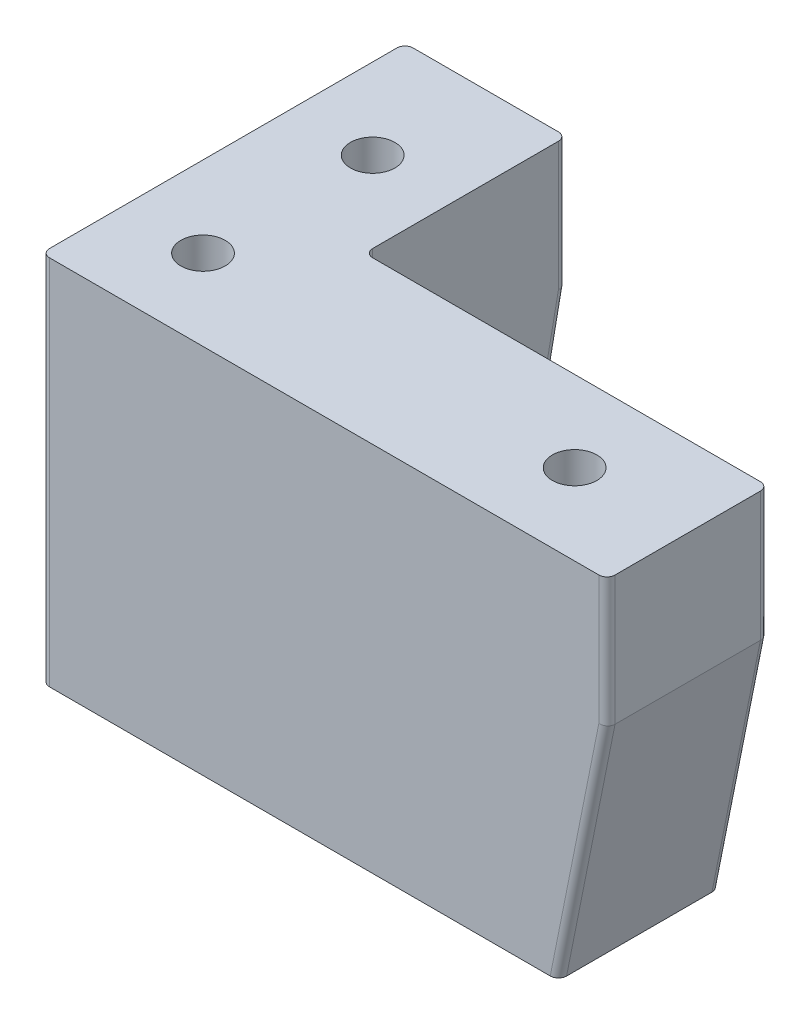
SolidWorks part; units mm, degrees
ref_plane "Front" through (0, 0, 0) normal (0, 0, 1) x (1, 0, 0)
ref_plane "Top" through (0, 0, 0) normal (0, 1, 0) x (1, 0, 0)
ref_plane "Right" through (0, 0, 0) normal (1, 0, 0) x (0, 0, -1)
sketch "Sketch1" plane through (0, 0, 0) normal (0, 1, 0) x (1, 0, 0)
  line L0 (0, 0) -> (70, 0)
  line L1 (70, 0) -> (70, 20)
  line L2 (70, 20) -> (20, 20)
  line L3 (20, 20) -> (20, 45)
  line L4 (20, 45) -> (0, 45)
  line L5 (0, 45) -> (0, 0)
  dimension "D1" = 70
  dimension "D2" = 45
  dimension "D3" = 20
extrude "Boss-Extrude1" add sketch "Sketch1" against normal blind 16
ref_plane "Plane1" through (0, -46, 0) normal (0, 1, 0) x (1, 0, 0)
sketch "Sketch5" plane through (0, -46, 0) normal (0, 1, 0) x (1, 0, 0)
  line L2 (0, 0) -> (64, 0)
  line L3 (0, 0) -> (70, 0) construction
  line L4 (0, 0) -> (0, 39)
  line L5 (0, 45) -> (0, 0) construction
  line L6 (0, 39) -> (20, 39)
  line L7 (20, 20) -> (20, 45) construction
  line L8 (20, 39) -> (20, 20)
  line L9 (20, 20) -> (64, 20)
  line L10 (70, 20) -> (20, 20) construction
  line L11 (64, 20) -> (64, 0)
  line L12 (20, 45) -> (0, 45) construction
  line L13 (70, 0) -> (70, 20) construction
  dimension "D1" = 6
  dimension "D2" = 6
loft "Loft1" add profiles "Sketch5" section face at (30, -16, -21.6667) section "Sketch5"
sketch "Sketch6" plane through (0, -46, 0) normal (0, -1, 0) x (1, 0, 0)
  line L0 (10, -39) -> (10, 0) construction
  line L1 (20, -39) -> (0, -39) construction
  line L2 (0, 0) -> (64, 0) construction
  line L3 (64, -10) -> (0, -10) construction
  line L4 (64, 0) -> (64, -20) construction
  line L5 (0, -39) -> (0, 0) construction
  circle A0 centre (56, -10) radius 5.2
  circle A1 centre (10, -10) radius 5.2
  circle A2 centre (10, -31) radius 5.2
  dimension "D1" = 10.4
  dimension "D3" = 8
  dimension "D2" = 8
extrude "Cut-Extrude2" cut sketch "Sketch6" against normal offset from surface (41 mm away) 5 up to face at (30, 0, -21.6667)
hole_wizard "M5 Clearance Hole1" positions "Sketch7" profile "Sketch9" hole size "M5" standard "ANSI Metric" end condition through all
sketch "Sketch7" plane through (0, -5, 0) normal (0, -1, 0) x (-1, 0, 0)
  point P0 (-10, 10)
  point P3 (-56, 10)
  point P6 (-10, 31)
sketch "Sketch9" plane through (10, -5, -10) normal (1, 0, 0) x (0, 0, -1)
  line L0 (0, 0) -> (0, 5)
  line L1 (0, 5) -> (2.75, 5)
  line L2 (2.75, 5) -> (2.75, 0)
  line L5 (2.75, 0) -> (0, 0)
  line L11 (0, -6.35) -> (0, 107.95) construction
  dimension "Thru Hole Dia." = 5.5
  dimension "Thru Hole Depth" = 5
fillet "Fillet2" radius 1 10 edges at (0, -8, -45) (20, -8, -45) (70, -8, -20) (70, -8, 0)
sketch "Sketch10" [suppressed] plane through (0, -40, 0) normal (0, 0, -1) x (-1, 0, 0)
  line L0 (-45, 32) -> (0, 32) construction
  line L2 (0, 0) -> (0, 40) construction
  line L3 (-45, 40) -> (-45, 30) construction
  line L4 (-1, 40) -> (-44, 40) construction
  text T0 "FRF-04" font "Century Gothic" height in points 18
  dimension "D1" = 8
extrude "FRF Part Num" [suppressed] cut sketch "Sketch10" along normal blind 0.4
sketch "Sketch11" [suppressed] plane through (0, -40, 0) normal (0, 0, -1) x (1, 0, 0)
  line L0 (45, -32) -> (0, -32) construction
  line L1 (0, 0) -> (0, -40) construction
  line L2 (45, -40) -> (45, -30) construction
  line L3 (1, -40) -> (44, -40) construction
  text T0 "BLF-04" font "Century Gothic" height in points 18
  dimension "D1" = 8
extrude "BLF Part Num" [suppressed] cut sketch "Sketch11" along normal blind 0.4
sketch "Sketch12" plane through (0, -40, 0) normal (1, 0, 0) x (0, -1, 0)
  line L0 (-32, 0) -> (-32, 45) construction
  line L1 (-24, 45) -> (-40, 45) construction
  line L2 (-40, 44) -> (-40, 1) construction
  text T0 "BRF-05" font "Century Gothic" height in points 20
  dimension "D1" = 8
extrude "BRF Part Num" cut sketch "Sketch12" along normal blind 0.4
sketch "Sketch13" [suppressed] plane through (0, -40, 0) normal (1, 0, 0) x (0, 1, 0)
  line L0 (32, 0) -> (32, -45) construction
  line L2 (40, 0) -> (-6, 0) construction
  line L3 (24, -45) -> (40, -45) construction
  line L4 (40, -44) -> (40, -1) construction
  text T0 "FLF-05" font "Century Gothic" height in points 18
  dimension "D1" = 8
extrude "FLF Part Num" [suppressed] cut sketch "Sketch13" along normal blind 0.4
equation "\"foot_width\"= 70"
equation "\"D1@Sketch1\"=\"foot_width\""
equation "\"foot_length\"= 45"
equation "\"D2@Sketch1\"=\"foot_length\""
equation "\"D2@Sketch5\"=\"D1@Sketch5\""
